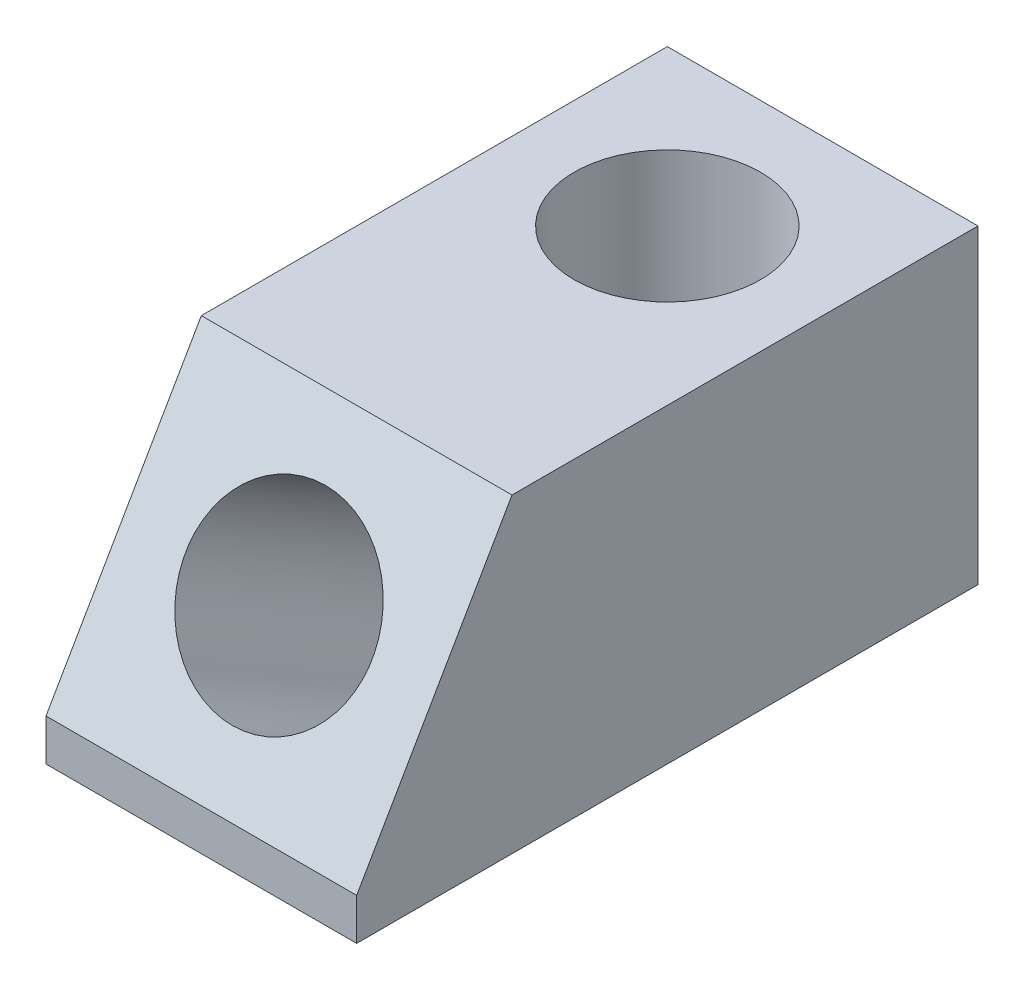
SolidWorks part; units mm, degrees
ref_plane "前视基准面" through (0, 0, 0) normal (0, 0, 1) x (1, 0, 0)
ref_plane "上视基准面" through (0, 0, 0) normal (0, 1, 0) x (1, 0, 0)
ref_plane "右视基准面" through (0, 0, 0) normal (1, 0, 0) x (0, 0, -1)
other "Configuration Table"
sketch "草图1" plane through (0, 0, 0) normal (0, 1, 0) x (1, 0, 0)
  line L1 (0, 0) -> (5, 0)
  line L2 (0, 0) -> (0, 10)
  line L3 (0, 10) -> (5, 10)
  line L4 (5, 0) -> (5, 10)
  circle A0 centre (2.5, 7.5) radius 1.5
  point P9 (7.3085, 2.0779)
  dimension "D3" = 3
  dimension "D1" = 5
  dimension "D2" = 10
  dimension "D4" = 7.5
  dimension "D5" = 2.5
extrude "凸台-拉伸1" add sketch "草图1" along normal blind 5
sketch "草图2" plane through (5, 0, 0) normal (1, 0, 0) x (0, 0, -1)
  line L0 (0, 0.6699) -> (2.5, 5)
  line L1 (0, 5) -> (0, 0) construction
  line L2 (0, 5) -> (10, 5) construction
  line L3 (0, 0.6699) -> (0, 5)
  line L4 (0, 5) -> (2.5, 5)
  dimension "D1" = 60
  dimension "D2" = 2.5
extrude "切除-拉伸1" cut sketch "草图2" against normal blind 5
sketch "草图3" plane through (0, 0.1675, 0.2901) normal (0, 0.5, 0.866) x (1, 0, 0)
  line L0 (5, 0.5801) -> (0, 5.5801) construction
  line L1 (0, 5.5801) -> (0, 0.5801)
  line L2 (0, 0.5801) -> (5, 5.5801) construction
  circle A0 centre (2.5, 3.0801) radius 1.5
  dimension "D1" = 3
extrude "切除-拉伸2" cut sketch "草图3" against normal through all contours A0
